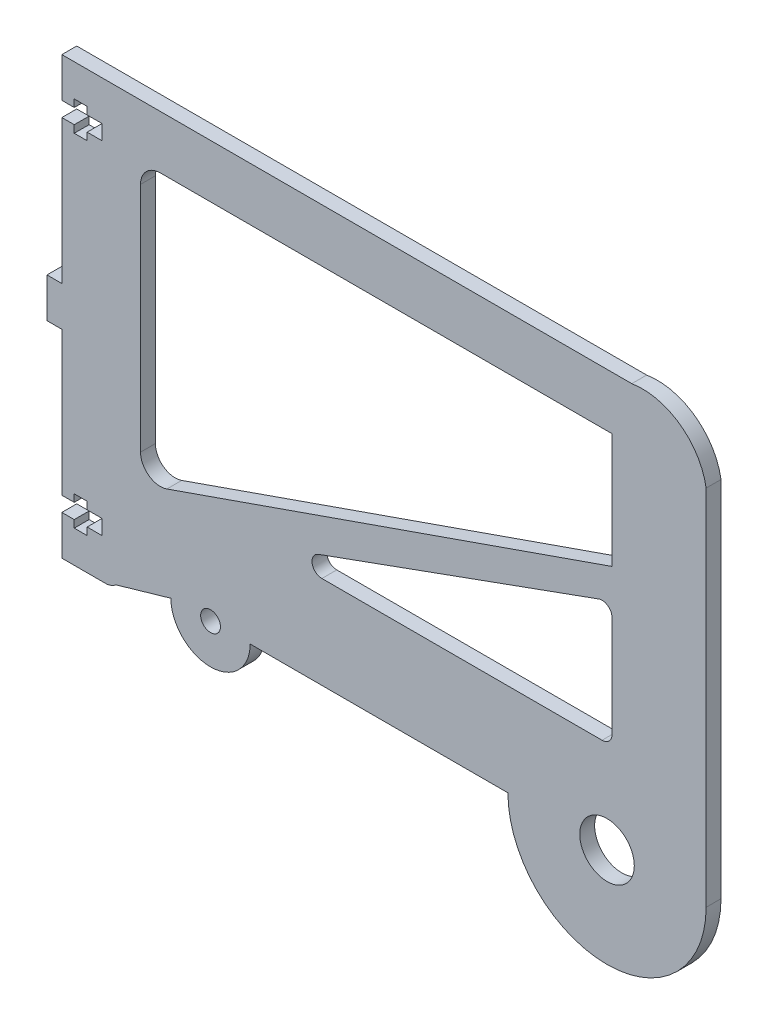
SolidWorks part; units mm, degrees
ref_plane "前视基准面" through (0, 0, 0) normal (0, 0, 1) x (1, 0, 0)
ref_plane "上视基准面" through (0, 0, 0) normal (0, 1, 0) x (1, 0, 0)
ref_plane "右视基准面" through (0, 0, 0) normal (1, 0, 0) x (0, 0, -1)
sketch "草图1" plane through (0, 0, 0) normal (0, 0, 1) x (1, 0, 0)
  line L308 (165.1949, 32.3961) -> (255.0026, 63.7655)
  line L334 (234.0026, 13.7079) -> (182.0026, 13.7079)
  line L360 (255.0026, 63.7655) -> (255.0026, 86.967)
  line L373 (274.0026, 13.7079) -> (274.0026, 86.967)
  line L374 (154.8509, 10.4846) -> (166.0026, 13.7079)
  line L394 (195.7931, 36.2767) -> (252.3219, 56.7376)
  line L395 (144.0026, 20.7079) -> (144.0026, 86.7079) construction
  line L396 (255.0026, 54.857) -> (255.0026, 34.3961)
  line L397 (159.8759, 82.967) -> (159.8759, 36.1724)
  line L398 (255.0026, 86.967) -> (163.8759, 86.967)
  line L399 (144.0026, 49.7079) -> (144.0026, 20.7079)
  line L400 (141.0026, 49.7079) -> (144.0026, 49.7079)
  line L401 (141.0026, 57.7079) -> (141.0026, 49.7079)
  line L402 (144.0026, 57.7079) -> (141.0026, 57.7079)
  line L403 (144.0026, 57.7079) -> (144.0026, 86.7079)
  line L404 (154.0026, 97.7079) -> (259.0026, 97.7079)
  line L405 (144.0026, 9.7079) -> (152.8367, 9.7079)
  line L406 (146.5026, 20.7079) -> (144.0026, 20.7079)
  line L407 (146.5026, 16.2079) -> (149.1026, 16.2079)
  line L408 (149.1026, 16.2079) -> (149.1026, 17.7079)
  line L409 (149.1026, 17.7079) -> (152.1026, 17.7079)
  line L410 (152.1026, 17.7079) -> (152.1026, 20.7079)
  line L411 (149.1026, 20.7079) -> (152.1026, 20.7079)
  line L412 (149.1026, 22.2079) -> (149.1026, 20.7079)
  line L413 (146.5026, 22.2079) -> (149.1026, 22.2079)
  line L414 (144.0026, 17.7079) -> (146.5026, 17.7079)
  line L415 (146.5026, 17.7079) -> (146.5026, 16.2079)
  line L416 (146.5026, 20.7079) -> (146.5026, 22.2079)
  line L417 (144.0026, 9.7079) -> (144.0026, 17.7079)
  line L418 (146.5026, 89.7079) -> (144.0026, 89.7079)
  line L419 (146.5026, 85.2079) -> (149.1026, 85.2079)
  line L420 (149.1026, 85.2079) -> (149.1026, 86.7079)
  line L421 (149.1026, 86.7079) -> (152.1026, 86.7079)
  line L422 (152.1026, 86.7079) -> (152.1026, 89.7079)
  line L423 (149.1026, 89.7079) -> (152.1026, 89.7079)
  line L424 (149.1026, 91.2079) -> (149.1026, 89.7079)
  line L425 (146.5026, 91.2079) -> (149.1026, 91.2079)
  line L426 (144.0026, 86.7079) -> (146.5026, 86.7079)
  line L427 (146.5026, 86.7079) -> (146.5026, 85.2079)
  line L428 (146.5026, 89.7079) -> (146.5026, 91.2079)
  line L429 (144.0026, 97.7079) -> (144.0026, 89.7079)
  line L430 (144.0026, 97.7079) -> (154.0026, 97.7079)
  line L431 (253.0026, 32.3961) -> (196.4738, 32.3961)
  circle A37 centre (174.0026, 13.7079) radius 2
  circle A38 centre (254.0026, 13.7079) radius 5.5
  circle A40 centre (174.0026, 13.7079) radius 8 construction
  arc A43 (259.0026, 97.7079) -> (274.0026, 86.967) centre (261.1322, 84.8374) cw
  arc A44 (274.0026, 13.7079) -> (234.0026, 13.7079) centre (254.0026, 13.7079) cw
  arc A59 (165.1949, 32.3961) -> (159.8759, 36.1724) centre (163.8759, 36.1724) cw
  arc A60 (163.8759, 86.967) -> (159.8759, 82.967) centre (163.8759, 82.967) ccw
  arc A61 (152.8367, 9.7079) -> (154.8509, 10.4846) centre (152.8367, 12.7079) ccw
  arc A62 (182.0026, 13.7079) -> (166.0026, 13.7079) centre (174.0026, 13.7079) cw
  arc A63 (195.7931, 36.2767) -> (196.4738, 32.3961) centre (196.4738, 34.3961) ccw
  arc A64 (255.0026, 54.857) -> (252.3219, 56.7376) centre (253.0026, 54.857) ccw
  arc A65 (255.0026, 34.3961) -> (253.0026, 32.3961) centre (253.0026, 34.3961) cw
  dimension "D1" = 2
  dimension "D2" = 2
extrude "凸台-拉伸1" add sketch "草图1" along normal blind 3
